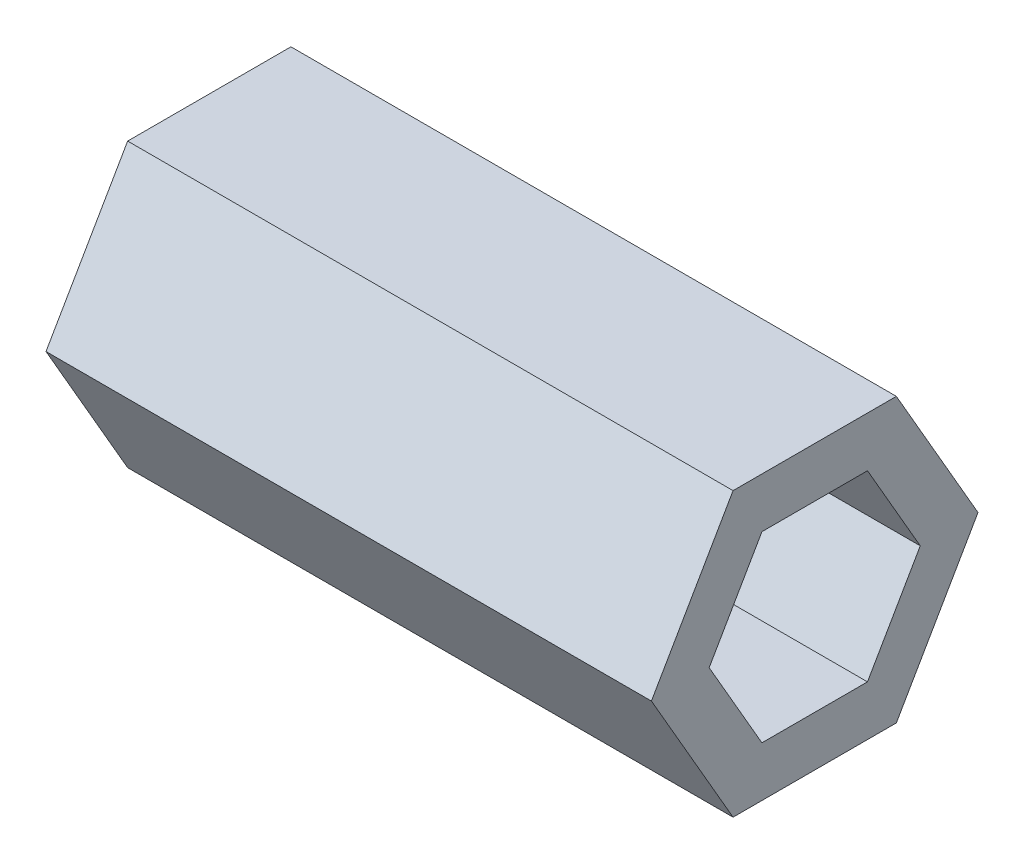
SolidWorks part; units mm, degrees
ref_plane "Front Plane" through (0, 0, 0) normal (0, 0, 1) x (1, 0, 0)
ref_plane "Top Plane" through (0, 0, 0) normal (0, 1, 0) x (1, 0, 0)
ref_plane "Right Plane" through (0, 0, 0) normal (1, 0, 0) x (0, 0, -1)
sketch "Sketch5" plane through (0, 0, 0) normal (1, 0, 0) x (0, 0, -1)
  line L1 (4, 0) -> (2, 3.4641)
  line L2 (2, 3.4641) -> (-2, 3.4641)
  line L3 (-2, 3.4641) -> (-4, 0)
  line L4 (-4, 0) -> (-2, -3.4641)
  line L5 (-2, -3.4641) -> (2, -3.4641)
  line L6 (2, -3.4641) -> (4, 0)
  circle A0 centre (0, 0) radius 4 construction
extrude "Boss-Extrude5" add sketch "Sketch5" along normal blind 25.4
sketch "Sketch7" plane through (25.4, 0, 0) normal (1, 0, 0) x (0, 0, -1)
  line L1 (6.1656, 0) -> (3.0828, 5.3395)
  line L2 (3.0828, 5.3395) -> (-3.0828, 5.3395)
  line L3 (-3.0828, 5.3395) -> (-6.1656, 0)
  line L4 (-6.1656, 0) -> (-3.0828, -5.3395)
  line L5 (-3.0828, -5.3395) -> (3.0828, -5.3395)
  line L6 (3.0828, -5.3395) -> (6.1656, 0)
  circle A0 centre (0, 0) radius 5.3395 construction
extrude "Boss-Extrude6" add sketch "Sketch7" against normal blind 22.86
sketch "Sketch8" plane through (0, 0, 0) normal (-1, 0, 0) x (0, 0, 1)
  line L1 (4, 0) -> (2, 3.4641)
  line L2 (2, 3.4641) -> (-2, 3.4641)
  line L3 (-2, 3.4641) -> (-4, 0)
  line L4 (-4, 0) -> (-2, -3.4641)
  line L5 (-2, -3.4641) -> (2, -3.4641)
  line L6 (2, -3.4641) -> (4, 0)
  circle A0 centre (0, 0) radius 3.4641 construction
extrude "Cut-Extrude2" cut sketch "Sketch8" against normal blind 10.16
sketch "Sketch10" plane through (2.54, 0, 0) normal (-1, 0, 0) x (0, 0, 1)
  line L0 (-2, 3.4641) -> (-3.0828, 5.3395)
sketch "Sketch11" plane through (25.4, 0, 0) normal (1, 0, 0) x (0, 0, -1)
  line L0 (3.0828, 5.3395) -> (0, 0)
  line L1 (3.0828, 5.3395) -> (1.9928, 3.4517)
sketch "Sketch12" plane through (25.4, 0, 0) normal (1, 0, 0) x (0, 0, -1)
  line L1 (1.9928, 3.4517) -> (-1.9928, 3.4517)
  line L2 (-1.9928, 3.4517) -> (-3.9857, 0)
  line L3 (-3.9857, 0) -> (-1.9928, -3.4517)
  line L4 (-1.9928, -3.4517) -> (1.9928, -3.4517)
  line L5 (1.9928, -3.4517) -> (3.9857, 0)
  line L6 (3.9857, 0) -> (1.9928, 3.4517)
  circle A0 centre (0, 0) radius 3.4517 construction
extrude "Cut-Extrude4" cut sketch "Sketch12" against normal blind 10.16
